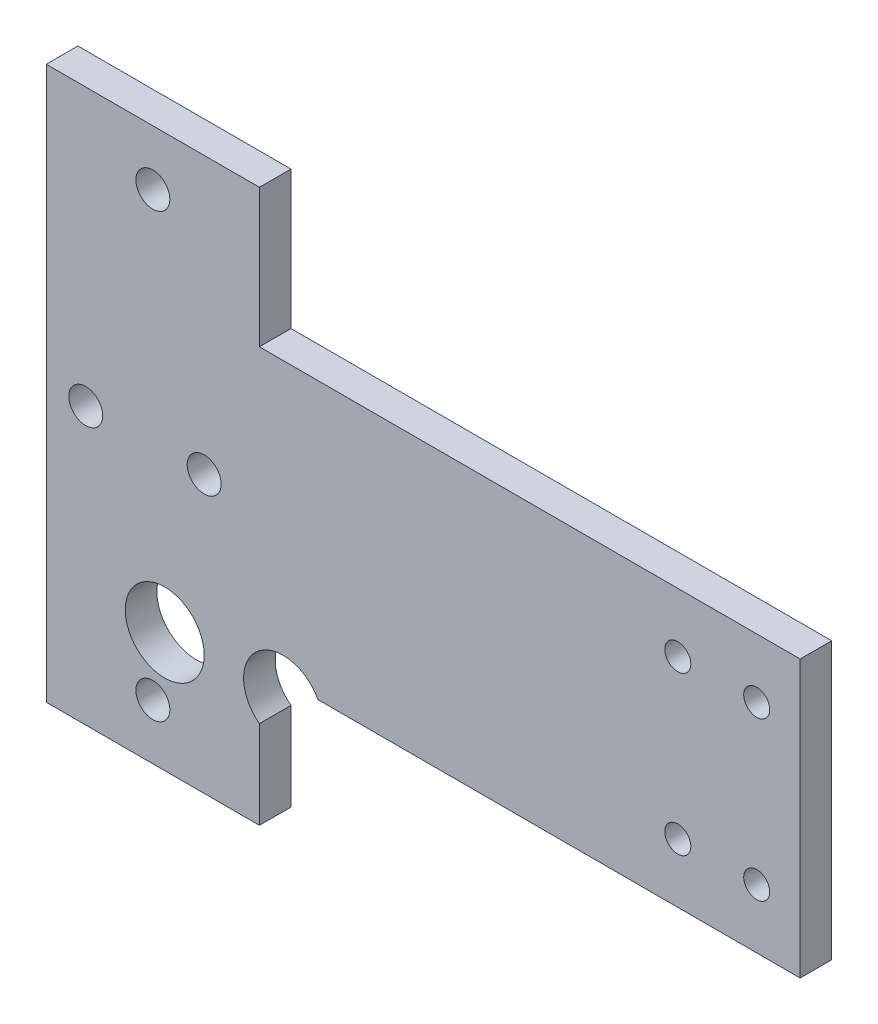
SolidWorks part; units mm, degrees
material "玻纤板"
ref_plane "前视基准面" through (0, 0, 0) normal (0, 0, 1) x (1, 0, 0)
ref_plane "上视基准面" through (0, 0, 0) normal (0, 1, 0) x (1, 0, 0)
ref_plane "右视基准面" through (0, 0, 0) normal (1, 0, 0) x (0, 0, -1)
other "Configuration Table"
sketch "草图1" plane through (0, 0, 0) normal (0, 0, 1) x (1, 0, 0)
  line L1 (0, 0) -> (100, 0)
  line L2 (0, 0) -> (0, -35)
  line L3 (0, -35) -> (100, -35)
  line L4 (100, 0) -> (100, -35)
  circle A0 centre (3, -15) radius 1.65 construction
  circle A1 centre (3, -35) radius 1.65 construction
  point P0 (0, 0)
  dimension "D1" = 20
  dimension "D2" = 3.3
  dimension "D5" = 3
  dimension "D6" = 15
  dimension "D3" = 100
  dimension "D4" = 35
extrude "凸台-拉伸1" add sketch "草图1" along normal blind 4
sketch "草图2" plane through (0, 0, 4) normal (0, 0, 1) x (1, 0, 0)
  line L0 (0, -17.5) -> (-35.4322, -17.5) construction
  line L1 (0, 0) -> (0, -35) construction
  circle A0 centre (80, -7.5) radius 1.65
  circle A1 centre (80, -27.5) radius 1.65
  dimension "D1" = 3.3
  dimension "D2" = 20
  dimension "D3" = 80
extrude "切除-拉伸1" cut sketch "草图2" against normal through all
sketch "草图3" plane through (0, 0, 4) normal (0, 0, 1) x (1, 0, 0)
  line L0 (20, -17.5) -> (50, -17.5) construction
  line L1 (20, -12.5) -> (50, -12.5)
  line L2 (20, -22.5) -> (50, -22.5)
  line L3 (0, -17.5) -> (-16.9458, -17.5) construction
  line L4 (0, 0) -> (0, -35) construction
  arc A0 (20, -12.5) -> (20, -22.5) centre (20, -17.5) ccw
  arc A1 (50, -22.5) -> (50, -12.5) centre (50, -17.5) ccw
  point P2 (35, -17.5)
  dimension "D1" = 5
  dimension "D2" = 30
  dimension "D3" = 20
extrude "切除-拉伸2" [suppressed] cut sketch "草图3" against normal through all
fillet "圆角2" [suppressed] radius 2
sketch "草图4" plane through (0, 0, 4) normal (0, 0, 1) x (1, 0, 0)
  line L0 (0, -17.5) -> (125.3825, -17.5) construction
  line L1 (0, 0) -> (0, -35) construction
  circle A0 centre (5, -17.5) radius 2.15
  circle A1 centre (20, -17.5) radius 2.15
  dimension "D1" = 5
  dimension "D2" = 15
  dimension "D3" = 4.3
extrude "切除-拉伸3" cut sketch "草图4" against normal through all
sketch "草图5" plane through (0, 0, 4) normal (0, 0, 1) x (1, 0, 0)
  line L0 (0, 0) -> (0, -35) construction
  line L2 (100, 0) -> (0, 0) construction
  line L3 (0, -17.5) -> (154.7179, -17.5) construction
  circle A0 centre (15, -7.5) radius 2.15
  circle A2 centre (100, -7.5) radius 1.65
  circle A3 centre (100, -27.5) radius 1.65
  circle A4 centre (15, -27.5) radius 2.15
  dimension "D1" = 15
  dimension "D2" = 20
  dimension "D3" = 4.3
  dimension "D4" = 3.3
  dimension "D5" = 100
  dimension "D6" = 7.5
extrude "切除-拉伸4" [suppressed] cut sketch "草图5" against normal through all
sketch "草图7" [suppressed] plane through (0, 0, 4) normal (0, 0, 1) x (1, 0, 0)
  line L0 (0, -17.5) -> (54.9435, -17.5) construction
  line L1 (0, -2) -> (0, -33) construction
  circle A0 centre (15, -17.5) radius 4
  circle A1 centre (15, -7.5) radius 2.15 construction
  circle A2 centre (15, -7.5) radius 2.15 construction
  circle A3 centre (30, -17.5) radius 4
  dimension "D1" = 15
  dimension "D2" = 8
extrude "切除-拉伸5" [suppressed] cut sketch "草图7" against normal through all
sketch "草图8" plane through (0, 0, 4) normal (0, 0, 1) x (1, 0, 0)
  line L0 (100, -17.5) -> (-17.2207, -17.5) construction
  line L1 (0, 17.5) -> (27, 17.5)
  line L2 (0, 17.5) -> (0, -52.5)
  line L3 (0, -52.5) -> (27, -52.5)
  line L4 (27, 17.5) -> (27, -52.5)
  line L5 (100, -35) -> (100, 0) construction
  line L6 (13.5, 17.5) -> (13.5, -79.2013) construction
  line L7 (0, 0) -> (0, -35) construction
  circle A0 centre (13.5, 10.5) radius 2.15
  circle A1 centre (13.5, -45.5) radius 2.15
  circle A2 centre (20, -17.5) radius 2.15 construction
  circle A3 centre (5, -17.5) radius 2.15 construction
  circle A4 centre (5, -17.5) radius 2.15
  circle A5 centre (20, -17.5) radius 2.15
  dimension "D1" = 56
  dimension "D2" = 4.3
  dimension "D4" = 13.5
  dimension "D3" = 70
extrude "凸台-拉伸2" add sketch "草图8" against normal blind 4
sketch "草图9" plane through (0, 0, 4) normal (0, 0, 1) x (1, 0, 0)
  line L0 (27, -35) -> (100, -35) construction
  line L1 (27, -52.5) -> (27, -35) construction
  circle A0 centre (30, -37.34) radius 5
  circle A1 centre (15, -37.34) radius 5
  dimension "D1" = 10
  dimension "D2" = 2.34
  dimension "D3" = 3
  dimension "D4" = 15
extrude "切除-拉伸6" cut sketch "草图9" against normal blind 4
sketch "草图10" plane through (0, 0, 4) normal (0, 0, 1) x (1, 0, 0)
  line L0 (80, -7.5) -> (100, -7.5) construction
  line L1 (100, -35) -> (100, 0) construction
  line L2 (80, -27.5) -> (100, -27.5) construction
  circle A0 centre (90, -7.5) radius 1.65
  circle A1 centre (90, -27.5) radius 1.65
  circle A2 centre (80, -27.5) radius 1.65 construction
  dimension "D1" = 10
extrude "切除-拉伸7" cut sketch "草图10" against normal blind 10
sketch "草图11" plane through (0, 0, 4) normal (0, 0, 1) x (1, 0, 0)
  line L0 (95.5, 0) -> (95.5, -35)
  line L1 (100, 0) -> (27, 0) construction
  line L2 (34.4186, -35) -> (100, -35) construction
  line L3 (95.5, -35) -> (100, -35)
  line L4 (100, -35) -> (100, 0)
  line L5 (100, 0) -> (95.5, 0)
  dimension "D1" = 4.5
extrude "切除-拉伸8" cut sketch "草图11" against normal blind 10
